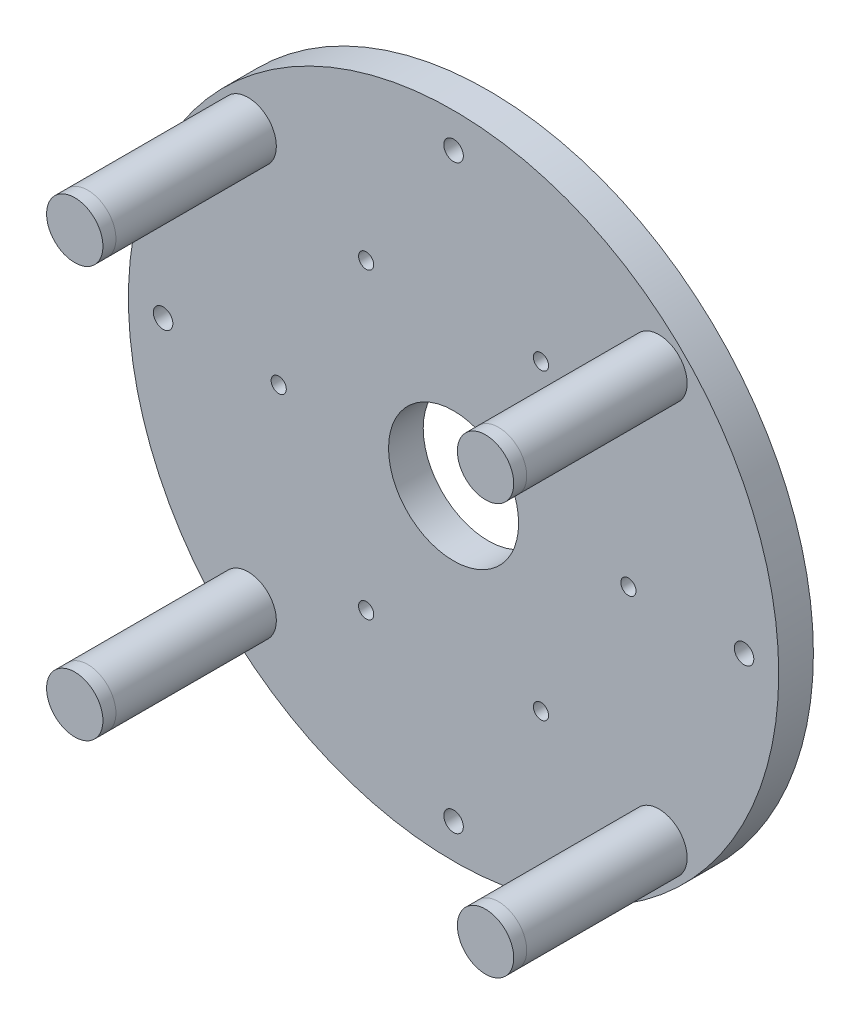
SolidWorks part; units mm, degrees
ref_plane "Ön Düzlem" through (0, 0, 0) normal (0, 0, 1) x (1, 0, 0)
ref_plane "Üst Düzlem" through (0, 0, 0) normal (0, 1, 0) x (1, 0, 0)
ref_plane "Sağ Düzlem" through (0, 0, 0) normal (1, 0, 0) x (0, 0, -1)
sketch "Sketch1" plane through (0, 0, 0) normal (0, 0, 1) x (1, 0, 0)
  circle A0 centre (0, 0) radius 75
  dimension "D1" = 150
extrude "Boss-Extrude1" add sketch "Sketch1" along normal blind 8
sketch "Sketch2" plane through (0, 0, 8) normal (0, 0, 1) x (1, 0, 0)
  line L0 (0, 0) -> (-53.033, 53.033) construction
  line L1 (0, 0) -> (0, 75) construction
  circle A0 centre (-47.3762, 47.3762) radius 6.5
  circle A1 centre (0, 0) radius 75 construction
  dimension "D1" = 13
  dimension "D2" = 67
  dimension "D3" = 45
extrude "Boss-Extrude2" add sketch "Sketch2" along normal blind 40
pattern_circular "CirPattern1" count 4 over 360 about axis through (0, 0, 0) along (0, 0, 1) of "Boss-Extrude2"
ref_plane "Plane1" through (0, 0, 45) normal (0, 0, 1) x (1, 0, 0)
split "Split1" trim tools "Plane1" bodies to split 103 resulting bodies 108 109 110 111 112
sketch "Sketch3" plane through (0, 0, 0) normal (0, 0, -1) x (-1, 0, 0)
  circle A0 centre (0, 0) radius 15
  dimension "D1" = 30
extrude "Cut-Extrude1" cut sketch "Sketch3" against normal through all
sketch "Sketch4" plane through (0, 0, 0) normal (0, 0, -1) x (-1, 0, 0)
  circle A0 centre (47.3762, 47.3762) radius 2.25
  circle A1 centre (47.3762, 47.3762) radius 6.5
  circle A2 centre (47.3762, 47.3762) radius 6.5 construction
  dimension "D2" = 4.5
  dimension "D1" = 0
extrude "Cut-Extrude2" cut sketch "Sketch4" against normal blind 10
pattern_circular "CirPattern2" count 8 over 360 about axis through (0, 0, 0) along (0, 0, 1) of "Cut-Extrude2"
sketch "Sketch5" plane through (0, 0, 0) normal (0, 0, -1) x (-1, 0, 0)
  circle A0 centre (0, 0) radius 40.33 construction
  circle A1 centre (-40.33, 0) radius 1.75
  dimension "D1" = 80.66
  dimension "D2" = 3.5
extrude "Cut-Extrude3" cut sketch "Sketch5" against normal through all
pattern_circular "CirPattern3" count 6 over 360 about axis through (0, 0, 0) along (0, 0, 1) of "Cut-Extrude3"
